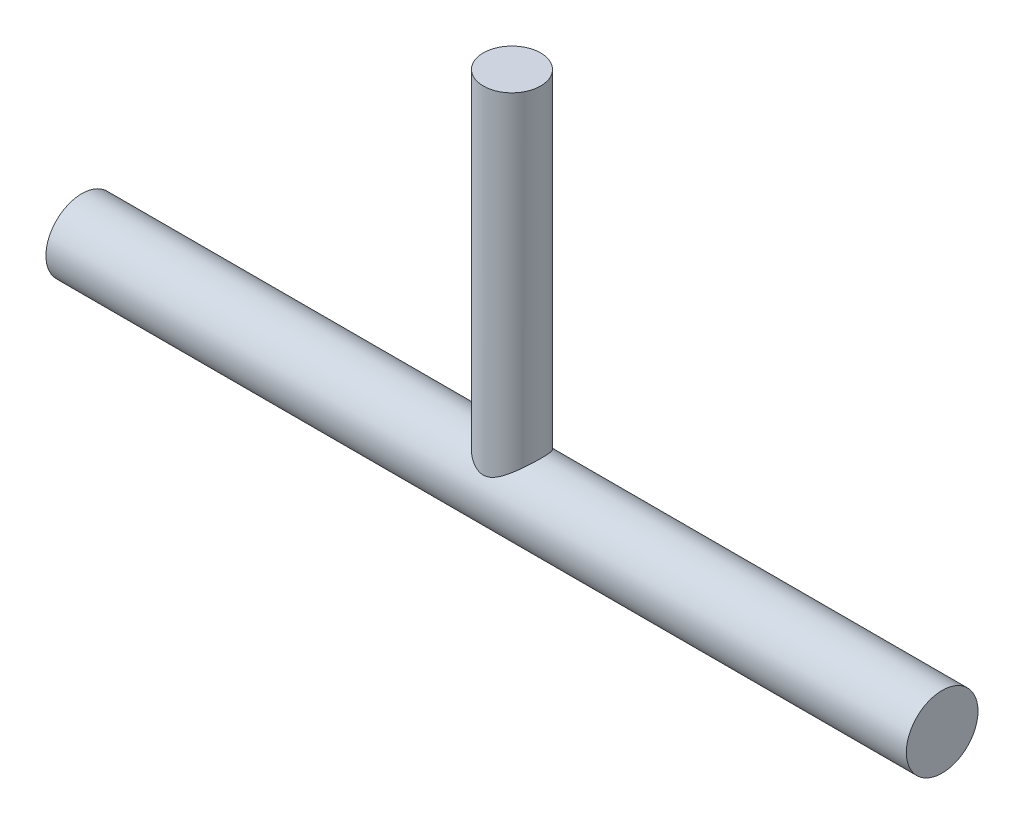
SolidWorks part; units mm, degrees
ref_plane "Front" through (0, 0, 0) normal (0, 0, 1) x (1, 0, 0)
ref_plane "Top" through (0, 0, 0) normal (0, 1, 0) x (1, 0, 0)
ref_plane "Right" through (0, 0, 0) normal (1, 0, 0) x (0, 0, -1)
sketch "草图1" plane through (0, 0, 0) normal (1, 0, 0) x (0, 0, -1)
  circle A0 centre (0, 0) radius 5
  dimension "D1" = 10
extrude "凸台-拉伸1" add sketch "草图1" along normal mid plane 120
sketch "草图2" plane through (0, 0, 0) normal (0, 1, 0) x (1, 0, 0)
  circle A0 centre (0, 0) radius 4
  dimension "D1" = 8
extrude "凸台-拉伸2" add sketch "草图2" along normal blind 50
move or copy body "实体-移动/复制1" bodies to move or copy 102 copy no translate (60, 0, 0)
